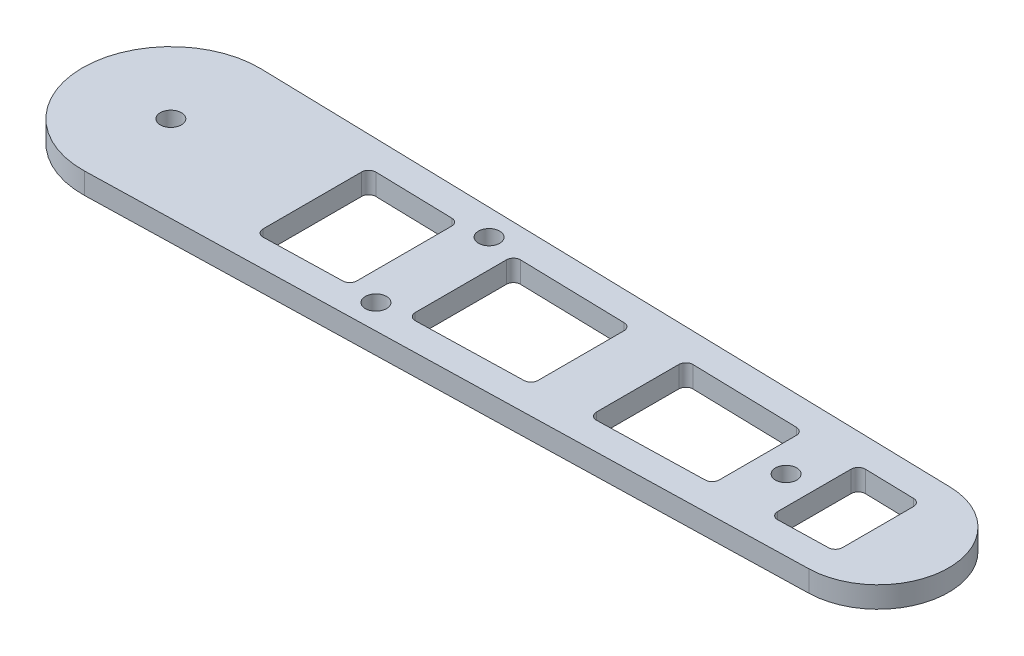
SolidWorks part; units mm, degrees
material "ABS"
ref_plane "前视基准面" through (0, 0, 0) normal (0, 0, 1) x (1, 0, 0)
ref_plane "上视基准面" through (0, 0, 0) normal (0, 1, 0) x (1, 0, 0)
ref_plane "右视基准面" through (0, 0, 0) normal (1, 0, 0) x (0, 0, -1)
sketch "草图1" plane through (0, 0, 0) normal (0, 1, 0) x (1, 0, 0)
  line L0 (-32.5011, 0) -> (135.0118, 0) construction
  line L1 (0.3125, 12.4961) -> (100.25, 9.9969)
  line L2 (0.3125, -12.4961) -> (100.25, -9.9969)
  circle A0 centre (0, 0) radius 12.5
  circle A1 centre (100, 0) radius 10
  circle A2 centre (0, 0) radius 1.5
  dimension "D1" = 25
  dimension "D2" = 20
  dimension "D4" = 3
  dimension "D3" = 100
extrude "凸台-拉伸1" add sketch "草图1" along normal blind 3 contours A0 L0 A2 | L0 A0 A2 | A0 L0 A1 L1 | L0 A0 L2 A1 | A1 L0 | L0 A1
sketch "草图2" plane through (0, 0, 0) normal (0, -1, 0) x (1, 0, 0)
  circle A0 centre (0, 0) radius 3
  circle A1 centre (0, 0) radius 4.5
  dimension "D1" = 6
  dimension "D2" = 9
extrude "凸台-拉伸2" add sketch "草图2" along normal blind 1.5
sketch "草图3" plane through (0, 3, 0) normal (0, 1, 0) x (1, 0, 0)
  line L0 (-22.3979, 0) -> (134.9394, 0) construction
  line L1 (20, 8.0025) -> (20, -8.0025)
  line L2 (20, 8.0025) -> (100, 6.0019)
  line L5 (0.3125, 12.4961) -> (100.25, 9.9969) construction
  line L6 (20, -8.0025) -> (100, -6.0019)
  line L7 (100, 6.0019) -> (100, -6.0019)
  line L8 (33, 7.6774) -> (33, -7.6774)
  line L9 (58, 7.0522) -> (58, -7.0522)
  line L10 (66, 6.8521) -> (66, -6.8521)
  line L11 (41, 7.4773) -> (41, -7.4773)
  line L12 (83, 6.427) -> (83, -6.427)
  line L13 (91, 6.2269) -> (91, -6.2269)
  circle A1 centre (37, 8) radius 1.5
  circle A2 centre (37, -8) radius 1.5
  circle A3 centre (87, 0) radius 1.5
  dimension "D5" = 8
  dimension "D7" = 3
  dimension "D13" = 3
  dimension "D1" = 20
  dimension "D2" = 4
  dimension "D3" = 33
  dimension "D4" = 8
  dimension "D6" = 37
  dimension "D9" = 58
  dimension "D10" = 8
  dimension "D11" = 83
  dimension "D12" = 8
  dimension "D14" = 4
  dimension "D15" = 100
extrude "切除-拉伸1" cut sketch "草图3" against normal blind 3 contours L1 L0 L8 L2 | L0 L1 L6 L8 | L2 A1 | L2 A1 | A2 L6 | A2 L6 | L11 L0 L9 L2 | L0 L11 L6 L9 | L10 L0 L12 L2 | L0 L10 L6 L12 | A3 L0 | L0 A3 | L13 L0 L7 L2 | L0 L13 L6 L7
fillet "圆角1" radius 1 16 edges at (91, 1.5, -6.2269) (91, 1.5, 6.2269) (100, 1.5, 6.0019) (100, 1.5, -6.0019) (83, 1.5, -6.427) (66, 1.5, -6.8521) (66, 1.5, 6.8521) (83, 1.5, 6.427) (58, 1.5, 7.0522) (41, 1.5, 7.4773) (58, 1.5, -7.0522) (41, 1.5, -7.4773) (33, 1.5, 7.6774) (33, 1.5, -7.6774) (20, 1.5, 8.0025) (20, 1.5, -8.0025)
